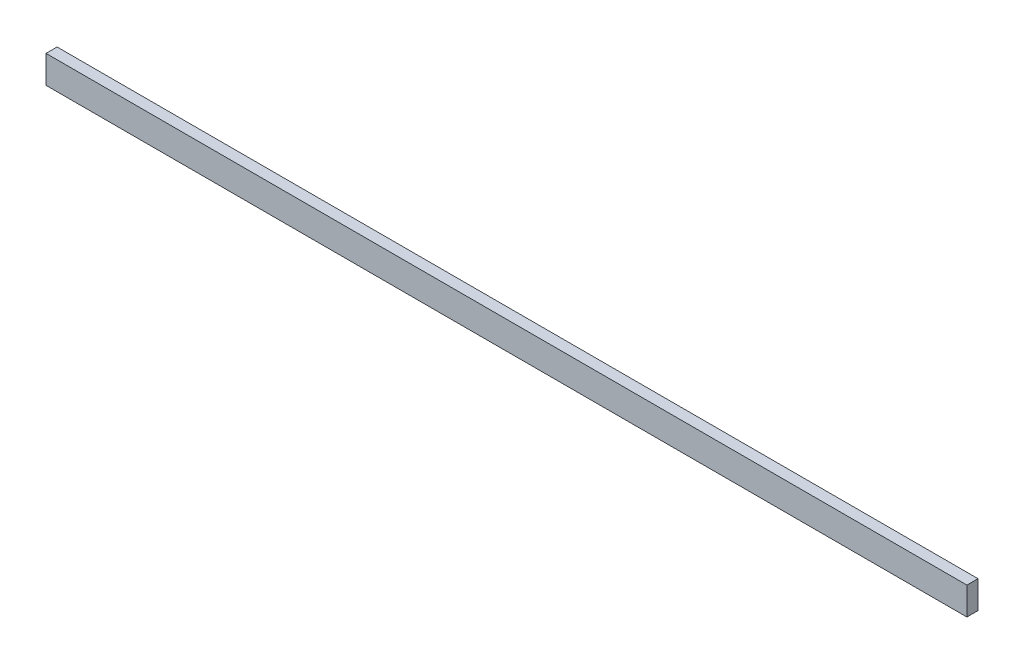
SolidWorks part; units mm, degrees
material "Plain Carbon Steel"
ref_plane "Front Plane" through (0, 0, 0) normal (0, 0, 1) x (1, 0, 0)
ref_plane "Top Plane" through (0, 0, 0) normal (0, 1, 0) x (1, 0, 0)
ref_plane "Right Plane" through (0, 0, 0) normal (1, 0, 0) x (0, 0, -1)
sketch "Sketch1" plane through (0, 0, 0) normal (0, 0, 1) x (1, 0, 0)
  line L1 (-332.5, -10) -> (332.5, -10)
  line L2 (-332.5, -10) -> (-332.5, 10)
  line L3 (-332.5, 10) -> (332.5, 10)
  line L4 (332.5, -10) -> (332.5, 10)
  line L5 (-332.5, -10) -> (332.5, 10) construction
  line L6 (-332.5, 10) -> (332.5, -10) construction
  point P0 (0, 0)
  dimension "D1" = 665
  dimension "D2" = 20
extrude "Boss-Extrude1" add sketch "Sketch1" along normal blind 8
